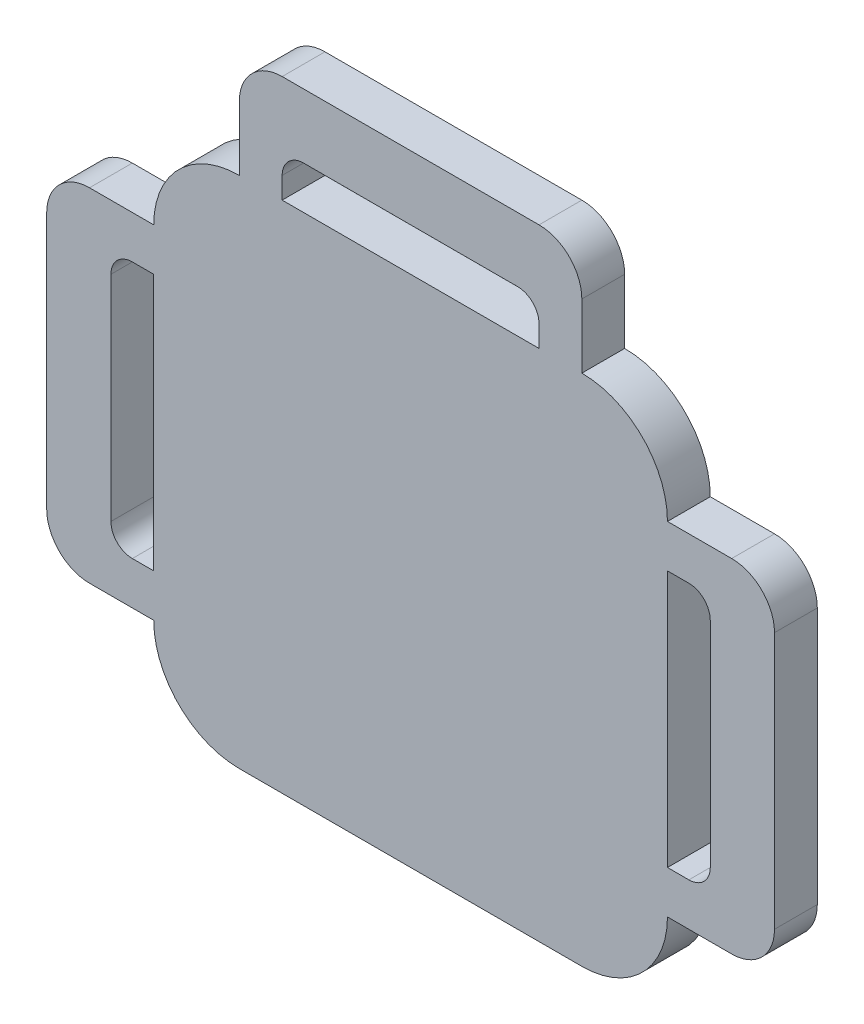
SolidWorks part; units mm, degrees
ref_plane "Front Plane" through (0, 0, 0) normal (0, 0, 1) x (1, 0, 0)
ref_plane "Top Plane" through (0, 0, 0) normal (0, 1, 0) x (1, 0, 0)
ref_plane "Right Plane" through (0, 0, 0) normal (1, 0, 0) x (0, 0, -1)
sketch "Sketch1" plane through (0, 0, 0) normal (0, 0, 1) x (1, 0, 0)
  line L0 (-87.8318, 31.5058) -> (-87.8318, 1.5058)
  line L1 (-77.8318, -13.4942) -> (-37.8318, -13.4942)
  line L3 (-72.8318, 46.5058) -> (-42.8318, 46.5058)
  line L5 (-27.8318, 36.5058) -> (-15.3318, 36.5058)
  line L6 (-27.8318, 31.5058) -> (-27.8318, 1.5058)
  line L7 (-27.8318, -3.4942) -> (-15.3318, -3.4942)
  line L8 (-15.3318, 36.5058) -> (-15.3318, -3.4942)
  line L9 (-27.8318, 31.5058) -> (-22.8318, 31.5058)
  line L11 (-27.8318, 1.5058) -> (-22.8318, 1.5058)
  line L12 (-22.8318, 31.5058) -> (-22.8318, 1.5058)
  line L13 (-92.8318, 31.5058) -> (-92.8318, 1.5058)
  line L14 (-87.8318, 1.5058) -> (-92.8318, 1.5058)
  line L15 (-87.8318, 31.5058) -> (-92.8318, 31.5058)
  line L16 (-100.3318, 36.5058) -> (-100.3318, -3.4942)
  line L17 (-87.8318, -3.4942) -> (-100.3318, -3.4942)
  line L18 (-87.8318, 36.5058) -> (-100.3318, 36.5058)
  line L19 (-77.8318, 46.5058) -> (-77.8318, 59.0058)
  line L20 (-77.8318, 59.0058) -> (-37.8318, 59.0058)
  line L21 (-37.8318, 59.0058) -> (-37.8318, 46.5058)
  line L22 (-72.8318, 46.5058) -> (-72.8318, 51.508)
  line L23 (-72.8318, 51.508) -> (-42.8318, 51.508)
  line L24 (-42.8318, 51.508) -> (-42.8318, 46.5058)
  arc A0 (-77.8318, -13.4942) -> (-87.8318, -3.4942) centre (-77.8318, -3.4942) cw
  arc A1 (-37.8318, -13.4942) -> (-27.8318, -3.4942) centre (-37.8318, -3.4942) ccw
  arc A2 (-27.8318, 36.5058) -> (-37.8318, 46.5058) centre (-37.8318, 36.5058) ccw
  arc A3 (-87.8318, 36.5058) -> (-77.8318, 46.5058) centre (-77.8318, 36.5058) cw
  point P32 (-27.8318, -13.4942)
  point P35 (-27.8318, 46.5058)
  dimension "D13" = 10
  dimension "D1" = 10
  dimension "D2" = 10
  dimension "D3" = 40
  dimension "D4" = 30
  dimension "D5" = 5
  dimension "D6" = 5
  dimension "D7" = 7.5
  dimension "D8" = 12.5
  dimension "D9" = 40
  dimension "D10" = 10
  dimension "D11" = 5
  dimension "D12" = 30
  dimension "D14" = 7.5
  dimension "D15" = 5
extrude "Boss-Extrude2" add sketch "Sketch1" along normal blind 5
fillet "Fillet1" radius 5 6 edges at (-15.3318, -3.4942, 2.5) (-15.3318, 36.5058, 2.5) (-37.8318, 59.0058, 2.5) (-77.8318, 59.0058, 2.5) (-100.3318, -3.4942, 2.5) (-100.3318, 36.5058, 2.5)
fillet "Fillet2" radius 2.5 6 edges at (-92.8318, 1.5058, 2.5) (-92.8318, 31.5058, 2.5) (-22.8318, 1.5058, 2.5) (-22.8318, 31.5058, 2.5) (-42.8318, 51.508, 2.5) (-72.8318, 51.508, 2.5)
